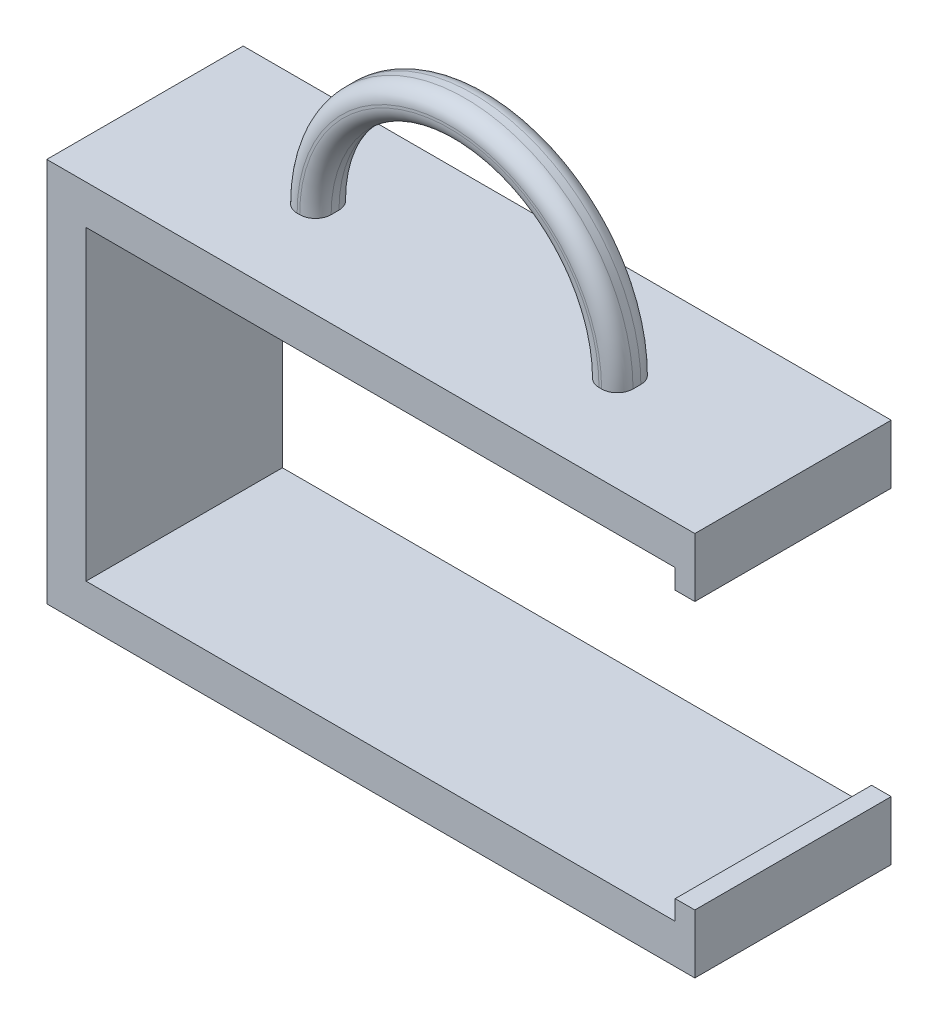
SolidWorks part; units mm, degrees
ref_plane "Front Plane" through (0, 0, 0) normal (0, 0, 1) x (1, 0, 0)
ref_plane "Top Plane" through (0, 0, 0) normal (0, 1, 0) x (1, 0, 0)
ref_plane "Right Plane" through (0, 0, 0) normal (1, 0, 0) x (0, 0, -1)
sketch "Sketch1" plane through (0, 0, 0) normal (0, 1, 0) x (1, 0, 0)
  line L1 (-41.25, -12.5) -> (41.25, -12.5)
  line L2 (-41.25, -12.5) -> (-41.25, 12.5)
  line L3 (-41.25, 12.5) -> (41.25, 12.5)
  line L4 (41.25, -12.5) -> (41.25, 12.5)
  line L5 (-41.25, -12.5) -> (41.25, 12.5) construction
  line L6 (-41.25, 12.5) -> (41.25, -12.5) construction
  point P0 (0, 0)
  dimension "D1" = 25
  dimension "D2" = 82.5
extrude "Boss-Extrude1" add sketch "Sketch1" along normal blind 5
sketch "Sketch2" plane through (0, 5, 0) normal (0, 1, 0) x (1, 0, 0)
  line L0 (-41.25, -12.5) -> (41.25, -12.5) construction
  line L1 (-41.25, 12.5) -> (-36.25, 12.5)
  line L2 (-41.25, 12.5) -> (-41.25, -12.5)
  line L3 (-41.25, -12.5) -> (-36.25, -12.5)
  line L4 (-36.25, 12.5) -> (-36.25, -12.5)
  dimension "D1" = 5
extrude "Boss-Extrude2" add sketch "Sketch2" along normal blind 39
sketch "Sketch3" plane through (0, 44, 0) normal (0, 1, 0) x (1, 0, 0)
  line L1 (41.25, 12.5) -> (-41.25, 12.5)
  line L2 (41.25, 12.5) -> (41.25, -12.5)
  line L3 (41.25, -12.5) -> (-41.25, -12.5)
  line L4 (-41.25, 12.5) -> (-41.25, -12.5)
extrude "Boss-Extrude3" add sketch "Sketch3" along normal blind 5
sketch "Sketch4" plane through (0, 0, 0) normal (0, 0, 1) x (1, 0, 0)
  line L0 (-41.25, 49) -> (41.25, 49) construction
  line L1 (-17.053, 49) -> (-21.3819, 49)
  line L2 (17.053, 49) -> (21.3819, 49)
  arc A0 (17.053, 49) -> (-17.053, 49) centre (0, 49) ccw
  arc A1 (-21.3819, 49) -> (21.3819, 49) centre (0, 49) cw
extrude "Boss-Extrude4" add sketch "Sketch4" along normal mid plane 5
sketch "Sketch5" plane through (0, 0, 12.5) normal (0, 0, 1) x (1, 0, 0)
  line L0 (-36.25, 44) -> (41.25, 44) construction
  line L1 (41.25, 5) -> (38.75, 5)
  line L2 (41.25, 5) -> (41.25, 44)
  line L3 (41.25, 44) -> (38.75, 44)
  line L4 (38.75, 5) -> (38.75, 44)
  dimension "D1" = 2.5
extrude "Boss-Extrude5" add sketch "Sketch5" against normal up to surface (25 mm away) up to face at (1.25, 24.5, -12.5)
sketch "Sketch6" plane through (0, 0, 12.5) normal (0, 0, 1) x (1, 0, 0)
  line L0 (41.25, 24.5) -> (41.1055, 24.5) construction
  line L1 (41.25, 49) -> (41.25, 0) construction
  line L2 (38.75, 44) -> (38.75, 5) construction
  line L3 (36.25, 7.5) -> (41.25, 7.5)
  line L4 (36.25, 7.5) -> (36.25, 41.5)
  line L5 (36.25, 41.5) -> (41.25, 41.5)
  line L6 (41.25, 7.5) -> (41.25, 41.5)
  line L7 (36.25, 7.5) -> (41.25, 41.5) construction
  line L8 (36.25, 41.5) -> (41.25, 7.5) construction
  point P4 (38.75, 24.5)
  dimension "D1" = 34
extrude "Cut-Extrude1" cut sketch "Sketch6" against normal up to surface (25 mm away) and the other way through all up to face at (1.25, 24.5, -12.5)
fillet "Fillet1" radius 2 2 edges at (0, 70.3819, -2.5) (0, 70.3819, 2.5)
fillet "Fillet2" radius 2 2 edges at (0, 66.053, -2.5) (0, 66.053, 2.5)
